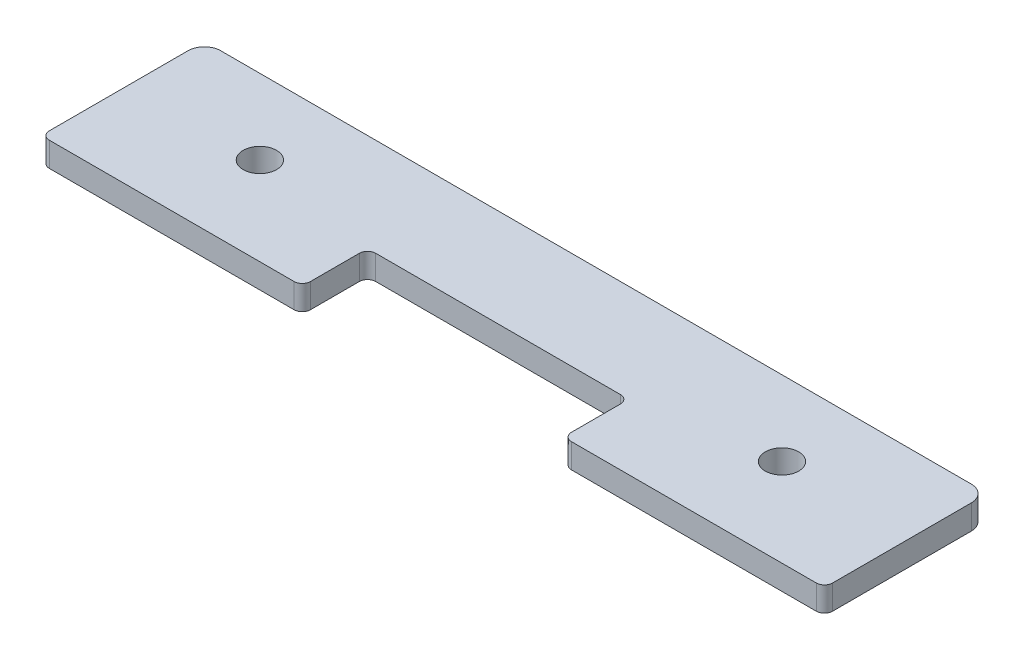
SolidWorks part; units mm, degrees
ref_plane "Front Plane" through (0, 0, 0) normal (0, 0, 1) x (1, 0, 0)
ref_plane "Top Plane" through (0, 0, 0) normal (0, 1, 0) x (1, 0, 0)
ref_plane "Right Plane" through (0, 0, 0) normal (1, 0, 0) x (0, 0, -1)
sketch "Sketch1" plane through (0, 0, 0) normal (0, 1, 0) x (1, 0, 0)
  line L0 (-4.7489, 0) -> (9.4274, 0) construction
  line L1 (0, -2.8184) -> (0, 6.8486) construction
  line L3 (46, 20) -> (-46, 20)
  line L6 (48, 18) -> (48, 1)
  line L7 (16, 1) -> (16, 7)
  line L8 (15, 8) -> (-15, 8)
  line L9 (47, 0) -> (17, 0)
  line L10 (-16, 1) -> (-16, 7)
  line L11 (-47, 0) -> (-17, 0)
  line L12 (-48, 18) -> (-48, 1)
  circle A0 centre (32, 10.8) radius 2.05
  arc A1 (48, 18) -> (46, 20) centre (46, 18) ccw
  circle A3 centre (-32, 10.8) radius 2.05
  arc A5 (-48, 18) -> (-46, 20) centre (-46, 18) cw
  arc A6 (48, 1) -> (47, 0) centre (47, 1) cw
  arc A7 (17, 0) -> (16, 1) centre (17, 1) cw
  arc A8 (16, 7) -> (15, 8) centre (15, 7) ccw
  arc A9 (-16, 7) -> (-15, 8) centre (-15, 7) cw
  arc A10 (-17, 0) -> (-16, 1) centre (-17, 1) ccw
  arc A11 (-48, 1) -> (-47, 0) centre (-47, 1) ccw
  point P12 (48, 20)
  point P14 (0, 20)
  point P15 (48, 0)
  point P25 (0, 0)
  point P30 (16, 0)
  point P33 (16, 8)
  point P40 (0, 8)
  dimension "D2" = 10.8
  dimension "D3" = 4.1
  dimension "D5" = 32
  dimension "D6" = 2
  dimension "D7" = 20
  dimension "D1" = 1
  dimension "D4" = 48
  dimension "D8" = 8
  dimension "D9" = 16
extrude "Boss-Extrude1" add sketch "Sketch1" along normal blind 3
